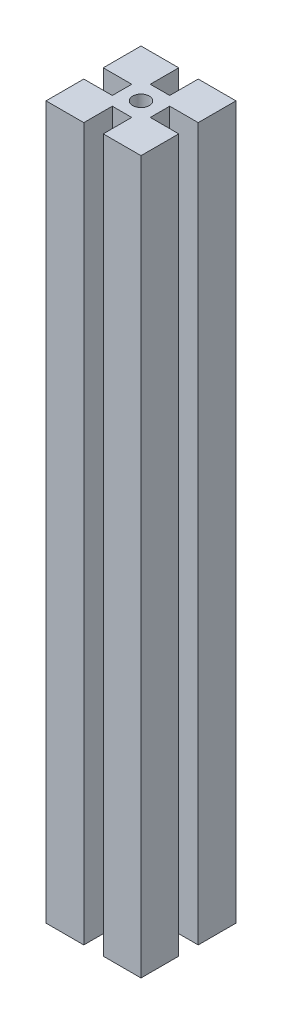
SolidWorks part; units mm, degrees
ref_plane "Ebene vorne" through (0, 0, 0) normal (0, 0, 1) x (1, 0, 0)
ref_plane "Ebene oben" through (0, 0, 0) normal (0, 1, 0) x (1, 0, 0)
ref_plane "Ebene rechts" through (0, 0, 0) normal (1, 0, 0) x (0, 0, -1)
sketch "Skizze1" plane through (0, 0, 0) normal (0, 1, 0) x (1, 0, 0)
  line L0 (-4.1, -20) -> (-4.1, -8)
  line L1 (-20, 20) -> (-4.1, 20)
  line L2 (-20, 20) -> (-20, 4.1)
  line L3 (-20, -20) -> (-4.1, -20)
  line L4 (20, 20) -> (20, 4.1)
  line L5 (-20, 20) -> (20, -20) construction
  line L6 (-20, -20) -> (20, 20) construction
  line L7 (-4.1, -8) -> (4.1, -8)
  line L8 (4.1, -8) -> (4.1, -20)
  line L9 (0, 53.9798) -> (0, -29.8049) construction
  line L10 (4.1, -20) -> (20, -20)
  line L11 (-42.3353, 0) -> (35.9872, 0) construction
  line L12 (4.1, 8) -> (4.1, 20)
  line L13 (-4.1, 20) -> (-4.1, 8)
  line L14 (-4.1, 8) -> (4.1, 8)
  line L15 (4.1, 20) -> (20, 20)
  line L16 (-20, 4.1) -> (-8, 4.1)
  line L17 (-8, 4.1) -> (-8, -4.1)
  line L18 (-8, -4.1) -> (-20, -4.1)
  line L19 (-20, -4.1) -> (-20, -20)
  line L20 (8, 4.1) -> (8, -4.1)
  line L21 (8, -4.1) -> (20, -4.1)
  line L22 (20, 4.1) -> (8, 4.1)
  line L23 (20, -4.1) -> (20, -20)
  circle A0 centre (0, 0) radius 3.5
  point P0 (0, 0)
  dimension "D7" = 7
  dimension "D1" = 40
  dimension "D2" = 8.2
  dimension "D3" = 12
  dimension "D4" = 40
  dimension "D5" = 8.2
  dimension "D6" = 12
extrude "Aufsatz-Linear austragen1" add sketch "Skizze1" along normal blind 300
